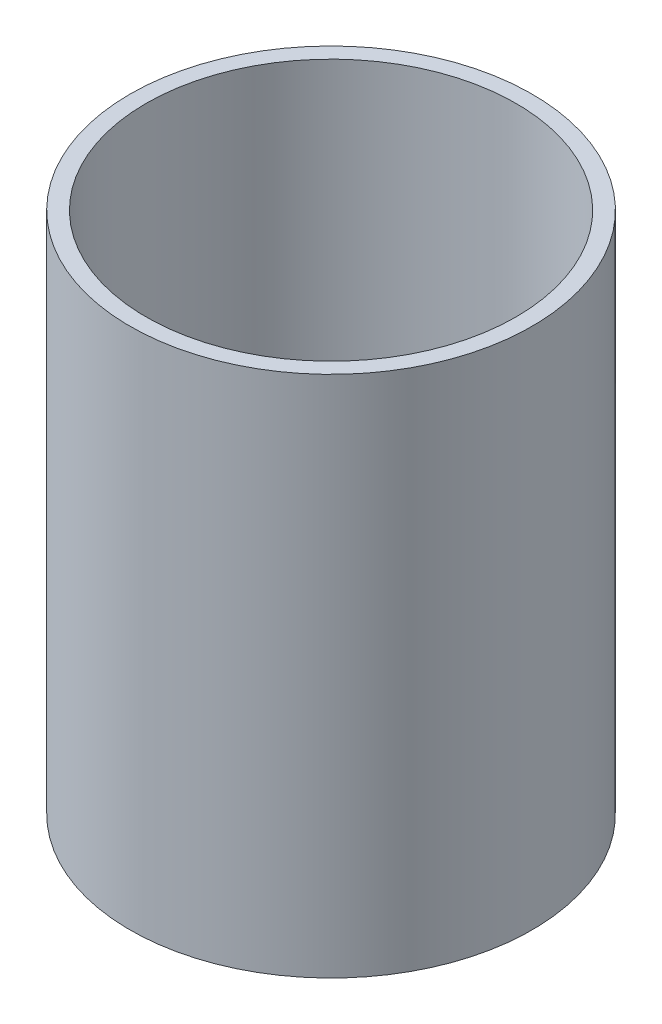
SolidWorks part; units mm, degrees
ref_plane "前视基准面" through (0, 0, 0) normal (0, 0, 1) x (1, 0, 0)
ref_plane "上视基准面" through (0, 0, 0) normal (0, 1, 0) x (1, 0, 0)
ref_plane "右视基准面" through (0, 0, 0) normal (1, 0, 0) x (0, 0, -1)
sketch "草图2" plane through (0, 0, 0) normal (0, 0, 1) x (1, 0, 0)
  line L0 (0, 0) -> (50, 0)
  line L1 (50, 0) -> (50, 130)
  line L2 (50, 130) -> (0, 130)
  line L3 (0, 130) -> (0, 0)
  dimension "D1" = 50
  dimension "D2" = 50
  dimension "D3" = 130
revolve "旋转1" add sketch "草图2" angle 360 about L3
shell "抽壳1" thickness 4
